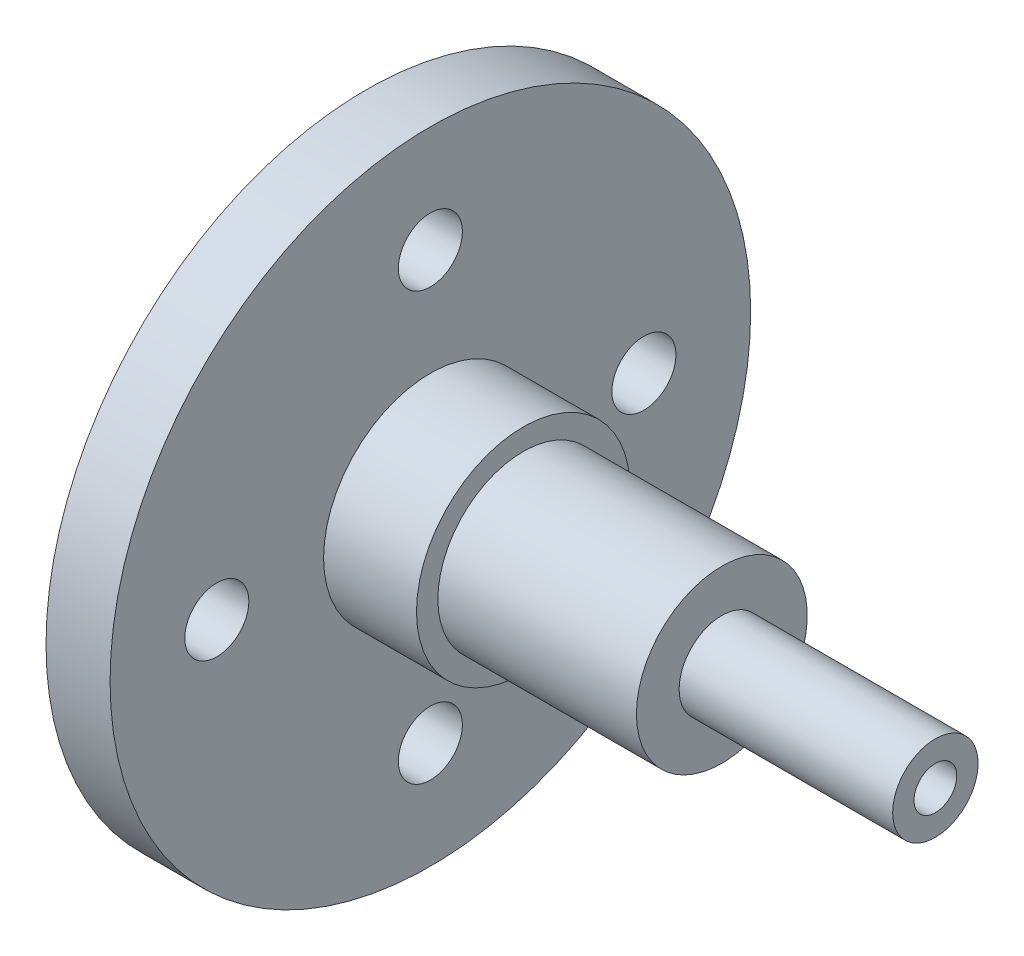
SolidWorks part; units mm, degrees
material "Alloy Steel"
ref_plane "Front Plane" through (0, 0, 0) normal (0, 0, 1) x (1, 0, 0)
ref_plane "Top Plane" through (0, 0, 0) normal (0, 1, 0) x (1, 0, 0)
ref_plane "Right Plane" through (0, 0, 0) normal (1, 0, 0) x (0, 0, -1)
sketch "Sketch1" plane through (0, 0, 0) normal (0, 0, 1) x (1, 0, 0)
  line L0 (-13.325, 0) -> (13.325, 0) construction
  line L7 (-13.325, 1) -> (-13.325, 15)
  line L10 (-13.325, 15) -> (-10.325, 15)
  line L11 (-10.325, 15) -> (-10.325, 5)
  line L12 (-10.325, 5) -> (-5.975, 5)
  line L13 (-5.975, 5) -> (-5.975, 4)
  line L14 (-5.975, 4) -> (3.325, 4)
  line L15 (3.325, 4) -> (3.325, 2)
  line L16 (3.325, 2) -> (13.325, 2)
  line L17 (13.325, 2) -> (13.325, 1)
  line L18 (-1.325, 4) -> (-1.325, 0) construction
  line L19 (13.325, 1) -> (-13.325, 1)
  point P3 (0, 0)
  point P23 (-11.825, 15)
  dimension "D1" = 9.3
  dimension "D2" = 12
  dimension "D3" = 3
  dimension "D4" = 8
  dimension "D5" = 10
  dimension "D6" = 30
  dimension "D7" = 2
  dimension "D8" = 4
  dimension "D9" = 10
revolve "Revolve1" add sketch "Sketch1" angle 360 about L0
sketch "Sketch2" plane through (-10.325, 0, 0) normal (1, 0, 0) x (0, 0, -1)
  line L0 (0, 0) -> (0, 10) construction
  circle A0 centre (0, 10) radius 1.5
  circle A1 centre (10, 0) radius 1.5
  circle A2 centre (0, -10) radius 1.5
  circle A3 centre (-10, 0) radius 1.5
  point P13 (0, 0)
  dimension "D1" = 3
  dimension "D2" = 10
  dimension "D4" = 10
  dimension "D5" = 10
  dimension "D3" = 4
extrude "Cut-Extrude1" cut sketch "Sketch2" against normal through all
